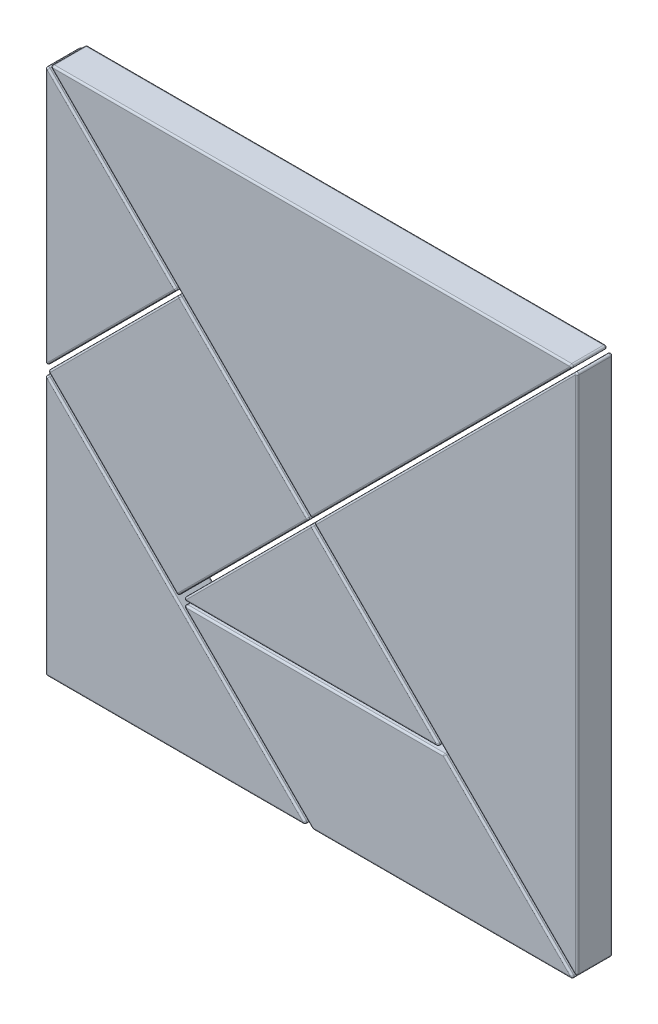
SolidWorks part; units mm, degrees
ref_plane "前视基准面" through (0, 0, 0) normal (0, 0, 1) x (1, 0, 0)
ref_plane "上视基准面" through (0, 0, 0) normal (0, 1, 0) x (1, 0, 0)
ref_plane "右视基准面" through (0, 0, 0) normal (1, 0, 0) x (0, 0, -1)
sketch "草图1" plane through (0, 0, 0) normal (0, 0, 1) x (1, 0, 0)
  line L0 (0, 150) -> (150, 0) construction
  line L1 (0, 0) -> (73.9393, 0)
  line L2 (0, 0) -> (0, 73.9393)
  line L3 (0.8839, 149.8232) -> (149.1161, 149.8232)
  line L4 (150, 0.7071) -> (150, 149.2929)
  line L5 (75, 75) -> (149.9116, 149.9116) construction
  line L6 (0, 74.6464) -> (74.6464, 0) construction
  line L7 (0, 149.2929) -> (36.9697, 112.3232)
  line L8 (37.3232, 37.3232) -> (112.6768, 37.3232) construction
  line L9 (37.3232, 37.3232) -> (75, 75) construction
  line L10 (0, 74.6464) -> (37.6768, 112.3232) construction
  line L11 (38.5303, 37.8232) -> (111.4697, 37.8232)
  line L12 (38.5303, 37.8232) -> (75, 74.2929)
  line L13 (75.7071, 75) -> (150, 149.2929)
  line L14 (0, 75.3536) -> (36.9697, 112.3232)
  line L15 (0, 73.9393) -> (73.9393, 0)
  line L16 (0.8839, 149.8232) -> (75, 75.7071)
  line L17 (75.3536, 0) -> (149.2929, 0)
  line L18 (0, 75.3536) -> (0, 149.2929)
  line L19 (75, 75.7071) -> (149.1161, 149.8232)
  line L20 (0.7071, 74.6464) -> (37.6768, 111.6161)
  line L21 (0.7071, 74.6464) -> (37.3232, 38.0303)
  line L22 (0.3536, 150.3536) -> (150.3536, 0.3536) construction
  line L23 (-0.3536, 149.6464) -> (149.6464, -0.3536) construction
  line L24 (75.3536, 74.6464) -> (150.2652, 149.5581) construction
  line L25 (74.6464, 75.3536) -> (149.5581, 150.2652) construction
  line L26 (75.7071, 75) -> (150, 0.7071)
  line L27 (38.5303, 37.8232) -> (75.3536, 74.6464) construction
  line L28 (75, 74.2929) -> (111.4697, 37.8232)
  line L29 (36.1161, 36.8232) -> (74.6464, 75.3536) construction
  line L30 (0.7071, 74.6464) -> (38.0303, 111.9697) construction
  line L31 (37.6768, 111.6161) -> (74.2929, 75)
  line L32 (-0.7071, 74.6464) -> (37.3232, 112.6768) construction
  line L33 (38.5303, 37.8232) -> (112.6768, 37.8232) construction
  line L34 (36.1161, 36.8232) -> (112.6768, 36.8232) construction
  line L35 (112.4697, 36.8232) -> (149.2929, 0)
  line L36 (-0.7071, 74.6464) -> (74.2929, -0.3536) construction
  line L37 (38.5303, 36.8232) -> (112.4697, 36.8232)
  line L38 (38.5303, 36.8232) -> (75.3536, 0)
  line L39 (0.7071, 74.6464) -> (75, 0.3536) construction
  line L40 (37.3232, 38.0303) -> (74.2929, 75)
  dimension "D1" = 150
  dimension "D2" = 150
  dimension "D5" = 73.9393
  dimension "D6" = 73.9393
  dimension "D7" = 73.9393
  dimension "D8" = 148.5858
  dimension "D9" = 1
  dimension "D14" = 148.2322
  dimension "D4" = 1
  dimension "D3" = 0.5
extrude "凸台-拉伸1" add sketch "草图1" along normal blind 10 contours L10 L6 L9 L0 | L9 L8 L0 | L18 L14 L7 | L16 L19 L3 | L13 L26 L4 | L37 L38 L17 L35 | L28 L12 L11 | L21 L40 L31 L20 | L15 L2 L1
fillet "圆角1" radius 0.5 1 edges at (37.6768, 111.6161, 5)
fillet "圆角2" radius 0.5 3 edges at (36.9697, 112.3232, 5) (0, 75.3536, 5) (0, 149.2929, 5)
fillet "圆角3" radius 0.5 3 edges at (75, 75.7071, 5) (149.1161, 149.8232, 5) (0.8839, 149.8232, 5)
fillet "圆角4" radius 0.5 3 edges at (150, 0.7071, 5) (75.7071, 75, 5) (150, 149.2929, 5)
fillet "圆角5" radius 0.5 3 edges at (74.2929, 75, 5) (37.3232, 38.0303, 5) (0.7071, 74.6464, 5)
fillet "圆角6" radius 0.5 3 edges at (111.4697, 37.8232, 5) (38.5303, 37.8232, 5) (75, 74.2929, 5)
fillet "圆角7" radius 0.5 3 edges at (73.9393, 0, 5) (0, 0, 5) (0, 73.9393, 5)
fillet "圆角8" radius 0.5 4 edges at (149.2929, 0, 5) (112.4697, 36.8232, 5) (38.5303, 36.8232, 5) (75.3536, 0, 5)
fillet "圆角9" radius 0.5 8 edges at (75.3693, 0.0381, 10) (57.2955, 18.0581, 10) (39.2755, 36.5146, 10) (76, 36.8232, 10) (112.4539, 36.7852, 10) (130.5277, 18.7652, 10) (148.5477, 0.3087, 10) (111.8232, 0, 10)
fillet "圆角10" radius 0.5 6 edges at (75.9142, 75, 10) (112.6036, 111.8964, 10) (149.6913, 148.5477, 10) (150, 75, 10) (149.6913, 1.4523, 10) (112.6036, 38.1036, 10)
fillet "圆角11" radius 0.5 6 edges at (1.6291, 149.5146, 10) (75, 149.8232, 10) (148.3709, 149.5146, 10) (111.8081, 112.5152, 10) (75, 75.9142, 10) (38.1919, 112.5152, 10)
fillet "圆角12" radius 0.5 6 edges at (39.2755, 38.1319, 10) (57.0152, 56.3081, 10) (75, 74.0858, 10) (92.9848, 56.3081, 10) (110.7245, 38.1319, 10) (75, 37.8232, 10)
fillet "圆角13" radius 0.5 8 edges at (37.3232, 38.2374, 10) (19.0152, 56.3384, 10) (0.9142, 74.6464, 10) (19.1919, 93.1313, 10) (37.6768, 111.409, 10) (55.9848, 93.3081, 10) (74.0858, 75, 10) (55.8081, 56.5152, 10)
fillet "圆角14" radius 0.5 6 edges at (0.3087, 76.0987, 10) (0, 112.3232, 10) (0.3087, 148.5477, 10) (18.7348, 130.5581, 10) (36.7626, 112.3232, 10) (18.7348, 94.0884, 10)
fillet "圆角15" radius 0.5 6 edges at (0.1464, 0.1464, 10) (0, 36.6161, 10) (0.3087, 73.1942, 10) (36.9697, 36.9697, 10) (73.1942, 0.3087, 10) (36.6161, 0, 10)
fillet "圆角16" radius 0.5 6 edges at (0.3087, 73.1942, 0) (0, 36.6161, 0) (0.1464, 0.1464, 0) (36.6161, 0, 0) (73.1942, 0.3087, 0) (36.9697, 36.9697, 0)
fillet "圆角17" radius 0.5 8 edges at (37.6768, 111.409, 0) (19.1919, 93.1313, 0) (0.9142, 74.6464, 0) (19.0152, 56.3384, 0) (37.3232, 38.2374, 0) (55.8081, 56.5152, 0) (74.0858, 75, 0) (55.9848, 93.3081, 0)
fillet "圆角18" radius 0.5 6 edges at (0.3087, 148.5477, 0) (0, 112.3232, 0) (0.3087, 76.0987, 0) (18.7348, 94.0884, 0) (36.7626, 112.3232, 0) (18.7348, 130.5581, 0)
fillet "圆角19" radius 0.5 6 edges at (148.3709, 149.5146, 0) (75, 149.8232, 0) (1.6291, 149.5146, 0) (38.1919, 112.5152, 0) (75, 75.9142, 0) (111.8081, 112.5152, 0)
fillet "圆角20" radius 0.5 6 edges at (149.6913, 148.5477, 0) (112.6036, 111.8964, 0) (75.9142, 75, 0) (112.6036, 38.1036, 0) (149.6913, 1.4523, 0) (150, 75, 0)
fillet "圆角21" radius 0.5 6 edges at (75, 74.0858, 0) (57.0152, 56.3081, 0) (39.2755, 38.1319, 0) (75, 37.8232, 0) (110.7245, 38.1319, 0) (92.9848, 56.3081, 0)
fillet "圆角22" radius 0.5 8 edges at (112.4539, 36.7852, 0) (76, 36.8232, 0) (39.2755, 36.5146, 0) (57.2955, 18.0581, 0) (75.3693, 0.0381, 0) (111.8232, 0, 0) (148.5477, 0.3087, 0) (130.5277, 18.7652, 0)
